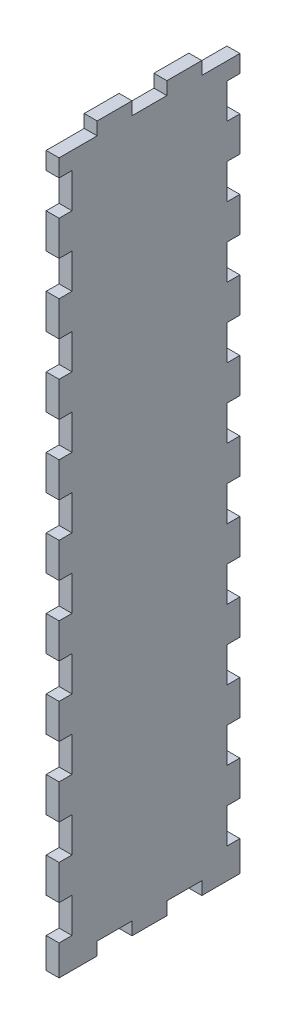
SolidWorks part; units mm, degrees
ref_plane "Front Plane" through (0, 0, 0) normal (0, 0, 1) x (1, 0, 0)
ref_plane "Top Plane" through (0, 0, 0) normal (0, 1, 0) x (1, 0, 0)
ref_plane "Right Plane" through (0, 0, 0) normal (1, 0, 0) x (0, 0, -1)
sketch "Sketch1" plane through (0, 0, 0) normal (1, 0, 0) x (0, 0, -1)
  line L0 (6.35, 355.6) -> (6.35, 349.25) construction
  line L1 (0, 0) -> (88.9, 0) construction
  line L2 (0, 0) -> (0, 6.35) construction
  line L3 (6.35, 355.6) -> (76.2, 355.6) construction
  line L4 (88.9, 0) -> (88.9, 6.35) construction
  line L5 (0, 6.35) -> (88.9, 6.35) construction
  line L6 (6.35, 349.25) -> (88.9, 349.25) construction
  line L7 (82.55, 355.6) -> (82.55, 338.1375) construction
  line L8 (0, 6.35) -> (0, 0)
  line L9 (0, 0) -> (6.35, 0)
  line L10 (6.35, 0) -> (18.7325, 0)
  line L11 (18.7325, 0) -> (18.7325, 6.35)
  line L12 (18.7325, 6.35) -> (35.8775, 6.35)
  line L13 (35.8775, 6.35) -> (35.8775, 0)
  line L14 (35.8775, 0) -> (53.0225, 0)
  line L15 (53.0225, 0) -> (53.0225, 6.35)
  line L16 (53.0225, 6.35) -> (70.1675, 6.35)
  line L17 (70.1675, 6.35) -> (70.1675, 0)
  line L18 (70.1675, 0) -> (82.55, 0)
  line L19 (82.55, 0) -> (88.9, 0)
  line L20 (88.9, 0) -> (88.9, 6.35)
  line L21 (6.35, 12.3825) -> (6.35, 0) construction
  line L22 (0, 0) -> (0, 349.25) construction
  line L23 (0, 6.35) -> (0, 14.9225)
  line L24 (0, 49.2125) -> (6.35, 49.2125)
  line L25 (6.35, 49.2125) -> (6.35, 66.3575)
  line L26 (6.35, 66.3575) -> (0, 66.3575)
  line L27 (0, 66.3575) -> (0, 83.5025)
  line L28 (0, 83.5025) -> (6.35, 83.5025)
  line L29 (6.35, 83.5025) -> (6.35, 100.6475)
  line L30 (6.35, 100.6475) -> (0, 100.6475)
  line L31 (0, 100.6475) -> (0, 117.7925)
  line L32 (0, 117.7925) -> (6.35, 117.7925)
  line L33 (6.35, 117.7925) -> (6.35, 134.9375)
  line L34 (6.35, 134.9375) -> (0, 134.9375)
  line L35 (0, 134.9375) -> (0, 152.0825)
  line L36 (0, 152.0825) -> (6.35, 152.0825)
  line L37 (6.35, 152.0825) -> (6.35, 169.2275)
  line L38 (6.35, 169.2275) -> (0, 169.2275)
  line L39 (0, 169.2275) -> (0, 186.3725)
  line L40 (0, 186.3725) -> (6.35, 186.3725)
  line L41 (6.35, 186.3725) -> (6.35, 203.5175)
  line L42 (6.35, 203.5175) -> (0, 203.5175)
  line L43 (0, 203.5175) -> (0, 220.6625)
  line L44 (0, 220.6625) -> (6.35, 220.6625)
  line L45 (6.35, 220.6625) -> (6.35, 237.8075)
  line L46 (6.35, 237.8075) -> (0, 237.8075)
  line L47 (0, 237.8075) -> (0, 254.9525)
  line L48 (0, 254.9525) -> (6.35, 254.9525)
  line L49 (6.35, 254.9525) -> (6.35, 272.0975)
  line L50 (6.35, 272.0975) -> (0, 272.0975)
  line L51 (0, 272.0975) -> (0, 289.2425)
  line L52 (0, 289.2425) -> (6.35, 289.2425)
  line L53 (6.35, 289.2425) -> (6.35, 306.3875)
  line L54 (6.35, 306.3875) -> (0, 306.3875)
  line L55 (0, 306.3875) -> (0, 323.5325)
  line L56 (0, 323.5325) -> (6.35, 323.5325)
  line L57 (6.35, 323.5325) -> (6.35, 329.692)
  line L58 (6.35, 340.6775) -> (0, 340.6775)
  line L59 (0, 340.6775) -> (0, 349.25)
  line L60 (6.35, 349.25) -> (0, 349.25)
  line L61 (6.35, 334.518) -> (6.35, 340.6775)
  line L62 (6.35, 349.25) -> (18.7325, 349.25)
  line L63 (18.7325, 349.25) -> (18.7325, 355.6)
  line L64 (18.7325, 355.6) -> (35.8775, 355.6)
  line L65 (35.8775, 355.6) -> (35.8775, 349.25)
  line L66 (35.8775, 349.25) -> (53.0225, 349.25)
  line L67 (53.0225, 349.25) -> (53.0225, 355.6)
  line L68 (53.0225, 355.6) -> (70.1675, 355.6)
  line L69 (70.1675, 355.6) -> (70.1675, 349.25)
  line L70 (70.1675, 349.25) -> (88.9, 349.25)
  line L71 (88.9, 6.35) -> (88.9, 14.9225)
  line L72 (88.9, 14.9225) -> (82.55, 14.9225)
  line L73 (82.55, 12.3825) -> (82.55, 0) construction
  line L74 (82.55, 14.9225) -> (82.55, 32.0675)
  line L75 (82.55, 32.0675) -> (88.9, 32.0675)
  line L76 (88.9, 32.0675) -> (88.9, 49.2125)
  line L77 (88.9, 66.3575) -> (88.9, 83.5025)
  line L78 (82.55, 66.3575) -> (88.9, 66.3575)
  line L79 (82.55, 49.2125) -> (82.55, 66.3575)
  line L80 (88.9, 49.2125) -> (82.55, 49.2125)
  line L81 (88.9, 100.6475) -> (88.9, 117.7925)
  line L82 (82.55, 100.6475) -> (88.9, 100.6475)
  line L83 (82.55, 83.5025) -> (82.55, 100.6475)
  line L84 (88.9, 83.5025) -> (82.55, 83.5025)
  line L85 (88.9, 134.9375) -> (88.9, 152.0825)
  line L86 (82.55, 134.9375) -> (88.9, 134.9375)
  line L87 (82.55, 117.7925) -> (82.55, 134.9375)
  line L88 (88.9, 117.7925) -> (82.55, 117.7925)
  line L89 (88.9, 169.2275) -> (88.9, 186.3725)
  line L90 (82.55, 169.2275) -> (88.9, 169.2275)
  line L91 (82.55, 152.0825) -> (82.55, 169.2275)
  line L92 (88.9, 152.0825) -> (82.55, 152.0825)
  line L93 (88.9, 203.5175) -> (88.9, 220.6625)
  line L94 (82.55, 203.5175) -> (88.9, 203.5175)
  line L95 (82.55, 186.3725) -> (82.55, 203.5175)
  line L96 (88.9, 186.3725) -> (82.55, 186.3725)
  line L97 (88.9, 237.8075) -> (88.9, 254.9525)
  line L98 (82.55, 237.8075) -> (88.9, 237.8075)
  line L99 (82.55, 220.6625) -> (82.55, 237.8075)
  line L100 (88.9, 220.6625) -> (82.55, 220.6625)
  line L101 (88.9, 272.0975) -> (88.9, 289.2425)
  line L102 (82.55, 272.0975) -> (88.9, 272.0975)
  line L103 (82.55, 254.9525) -> (82.55, 272.0975)
  line L104 (88.9, 254.9525) -> (82.55, 254.9525)
  line L105 (88.9, 306.3875) -> (88.9, 323.5325)
  line L106 (82.55, 306.3875) -> (88.9, 306.3875)
  line L107 (82.55, 289.2425) -> (82.55, 306.3875)
  line L108 (88.9, 289.2425) -> (82.55, 289.2425)
  line L109 (88.9, 340.6775) -> (88.9, 349.25)
  line L110 (82.55, 340.6775) -> (88.9, 340.6775)
  line L111 (88.9, 6.35) -> (88.9, 0)
  line L112 (82.55, 323.5325) -> (82.55, 340.6775)
  line L113 (0, 46.6725) -> (0, 49.2125) construction
  line L114 (88.9, 323.5325) -> (82.55, 323.5325)
  line L115 (0, 14.9225) -> (6.35, 14.9225)
  line L116 (6.35, 14.9225) -> (6.35, 21.082)
  line L117 (6.35, 32.0675) -> (0, 32.0675)
  line L118 (0, 32.0675) -> (0, 49.2125)
  line L119 (6.35, 334.518) -> (6.35, 329.692)
  line L127 (0, 177.8) -> (88.9237, 177.8) construction
  line L128 (6.35, 25.908) -> (6.35, 21.082)
  line L135 (6.35, 25.908) -> (6.35, 32.0675)
  dimension "D2" = 10
  dimension "D3" = 6.35
  dimension "D4" = 6.35
  dimension "D5" = 6.35
  dimension "D6" = 6.35
  dimension "D7" = 12.3825
  dimension "D8" = 17.145
  dimension "D9" = 17.145
  dimension "D10" = 12.3825
  dimension "D11" = 8.5725
  dimension "D12" = 10
  dimension "D17" = 6.35
  dimension "D18" = 17.145
  dimension "D19" = 12.3825
  dimension "D20" = 17.145
  dimension "D21" = 17.145
  dimension "D22" = 17.145
  dimension "D23" = 18.7325
extrude "Boss-Extrude1" add sketch "Sketch1" along normal blind 6.35
